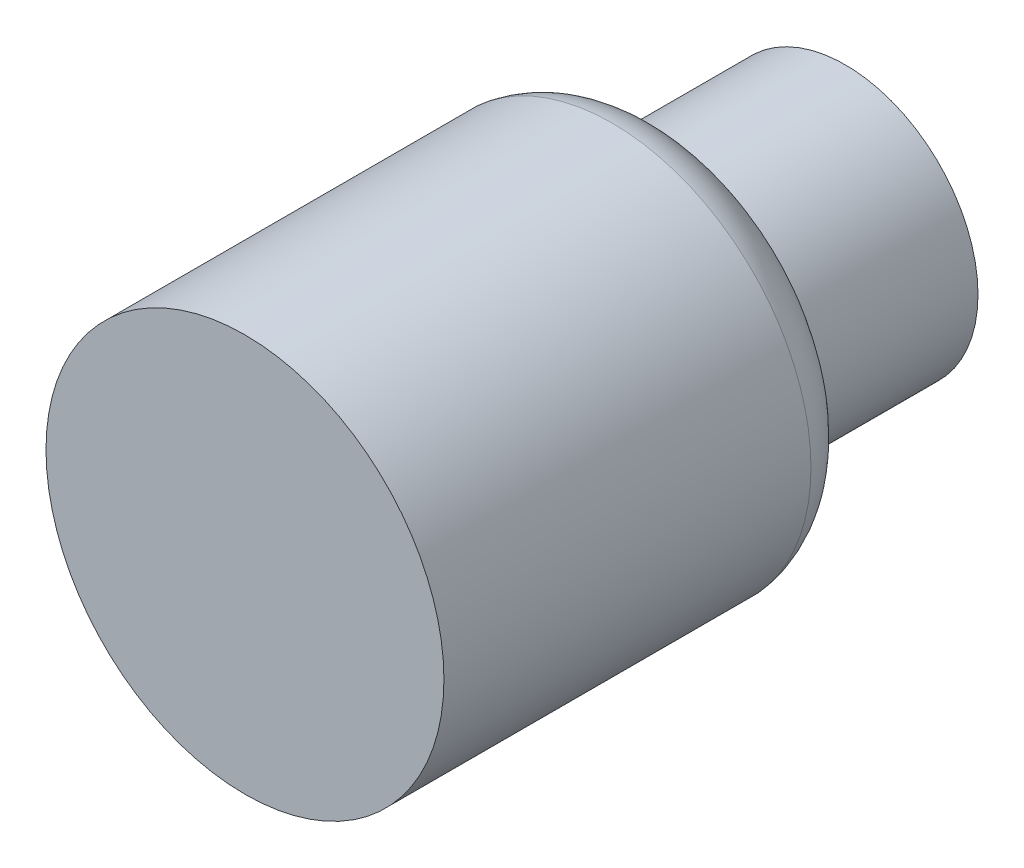
SolidWorks part; units mm, degrees
ref_plane "Front Plane" through (0, 0, 0) normal (0, 0, 1) x (1, 0, 0)
ref_plane "Top Plane" through (0, 0, 0) normal (0, 1, 0) x (1, 0, 0)
ref_plane "Right Plane" through (0, 0, 0) normal (1, 0, 0) x (0, 0, -1)
sketch "Sketch1" plane through (0, 0, 0) normal (0, 1, 0) x (1, 0, 0)
  line L0 (32.4187, -68.5342) -> (0, -68.5342)
  line L1 (21.6124, 0) -> (21.6124, 29.2905)
  line L2 (21.6124, 29.2905) -> (0, 29.2905)
  line L3 (32.4187, -68.5342) -> (32.4187, -8.7324)
  line L4 (0, 39.3384) -> (0, -74.4112) construction
  line L5 (0, -68.5342) -> (0, 29.2905)
  arc A1 (21.6124, 0) -> (32.4187, -8.7324) centre (22.3699, -10.1152) cw
  point P0 (0, 0)
revolve "Revolve1" add sketch "Sketch1" angle 360 about L4
